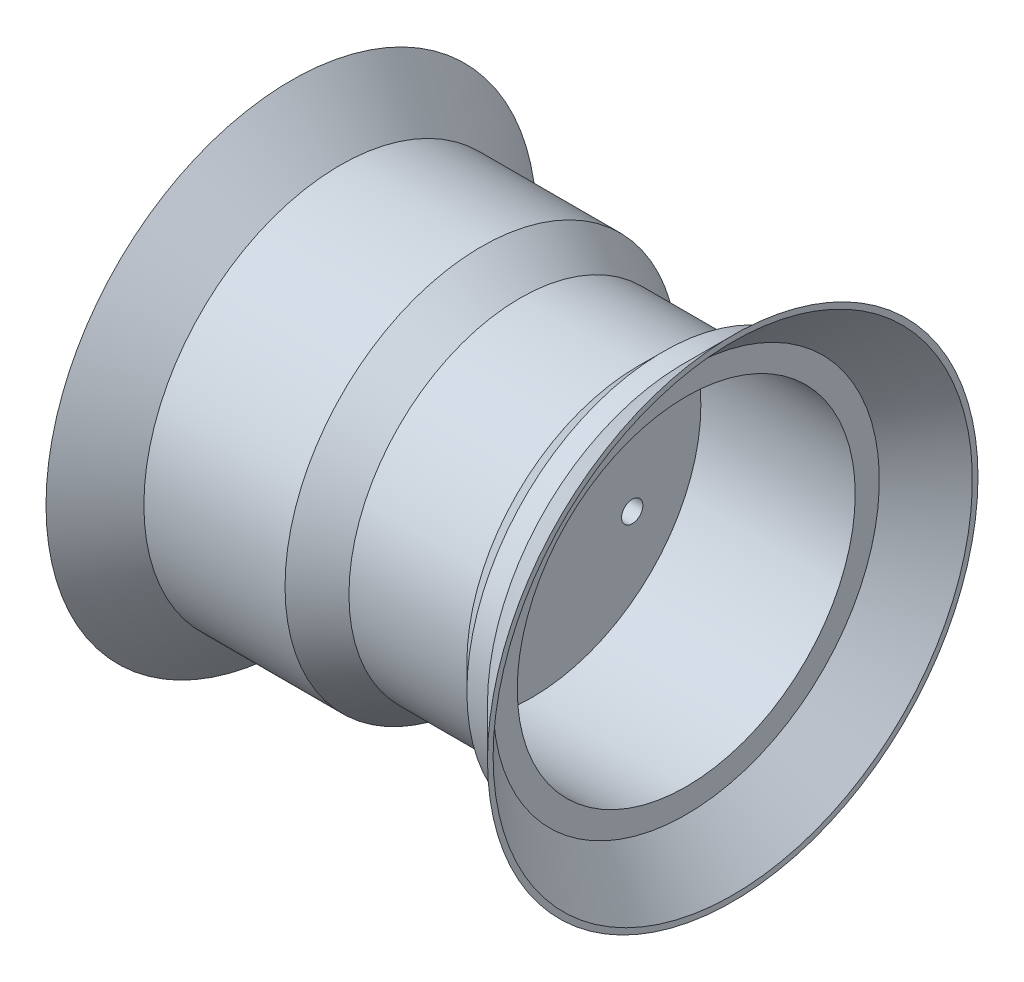
SolidWorks part; units mm, degrees
ref_plane "Front Plane" through (0, 0, 0) normal (0, 0, 1) x (1, 0, 0)
ref_plane "Top Plane" through (0, 0, 0) normal (0, 1, 0) x (1, 0, 0)
ref_plane "Right Plane" through (0, 0, 0) normal (1, 0, 0) x (0, 0, -1)
sketch "Sketch2" plane through (0, 0, 0) normal (0, 0, 1) x (1, 0, 0)
  line L0 (0, 0) -> (0, 63.5)
  line L1 (0, 0) -> (114.3, 0)
  line L3 (114.3, 63.5) -> (114.3, 0)
  line L4 (12.6714, 50.8286) -> (49.2146, 50.8286)
  line L6 (0, 63.5) -> (12.6714, 50.8286)
  line L7 (59.2702, 44.337) -> (89.8029, 44.337)
  line L8 (114.3, 63.5) -> (101.6286, 50.8286)
  line L9 (89.8029, 44.337) -> (96.2945, 50.8286)
  line L10 (96.2945, 50.8286) -> (101.6286, 50.8286)
  line L11 (49.2146, 50.8286) -> (59.2702, 44.337)
revolve "Revolve1" add sketch "Sketch2" angle 360 about L1
sketch "Sketch3" plane through (0, 0, 0) normal (-1, 0, 0) x (0, 0, 1)
  circle A0 centre (0, 0) radius 50
extrude "Cut-Extrude1" cut sketch "Sketch3" against normal blind 48
sketch "Sketch4" plane through (114.3, 0, 0) normal (1, 0, 0) x (0, 0, -1)
  circle A0 centre (0, 0) radius 43.75
extrude "Cut-Extrude2" cut sketch "Sketch4" against normal blind 52
sketch "Sketch5" plane through (0, 0, 0) normal (0, 0, 1) x (1, 0, 0)
  line L1 (12.0413, 50) -> (-0.2778, 62.319)
  line L2 (-0.2778, 62.319) -> (-0.2778, 50)
  line L5 (0, 0) -> (118.8676, 0) construction
  line L6 (114.5778, 62.319) -> (114.5778, 50)
  line L7 (102.2587, 50) -> (114.5778, 62.319)
  line L8 (12.0413, 50) -> (-0.2778, 50)
  line L9 (102.2587, 50) -> (102.2587, 45.7969)
  line L10 (114.5778, 50) -> (114.5778, 45.7969)
  line L13 (102.2587, 45.7969) -> (102.2587, 42.1742)
  line L14 (114.5778, 45.7969) -> (114.5778, 42.1742)
  line L15 (114.5778, 42.1742) -> (102.2587, 42.1742)
revolve "Cut-Revolve1" cut sketch "Sketch5" angle 360 about L5
sketch "Sketch6" plane through (0, 0, 0) normal (0, 0, 1) x (1, 0, 0)
  line L0 (55.7062, 41.7413) -> (47.1249, 41.7413)
  line L2 (47.1249, 41.7413) -> (47.1249, 49.7398)
  line L4 (0, 0) -> (118.0186, 0) construction
  line L5 (47.1249, 49.7398) -> (55.7062, 41.7413)
revolve "Cut-Revolve2" cut sketch "Sketch6" angle 360 about L4
sketch "Sketch7" plane through (48, 0, 0) normal (-1, 0, 0) x (0, 0, 1)
  circle A0 centre (0, 0) radius 43.75
extrude "Cut-Extrude3" cut sketch "Sketch7" against normal blind 10
sketch "Sketch8" plane through (62.3, 0, 0) normal (1, 0, 0) x (0, 0, -1)
  circle A0 centre (0, 0) radius 11.625
  circle A2 centre (0, 30) radius 2.75
  circle A3 centre (25.9808, -15) radius 2.75
  circle A4 centre (-25.9808, -15) radius 2.75
  point P13 (0, 0)
  dimension "D1" = 3
extrude "Cut-Extrude4" cut sketch "Sketch8" against normal blind 10
